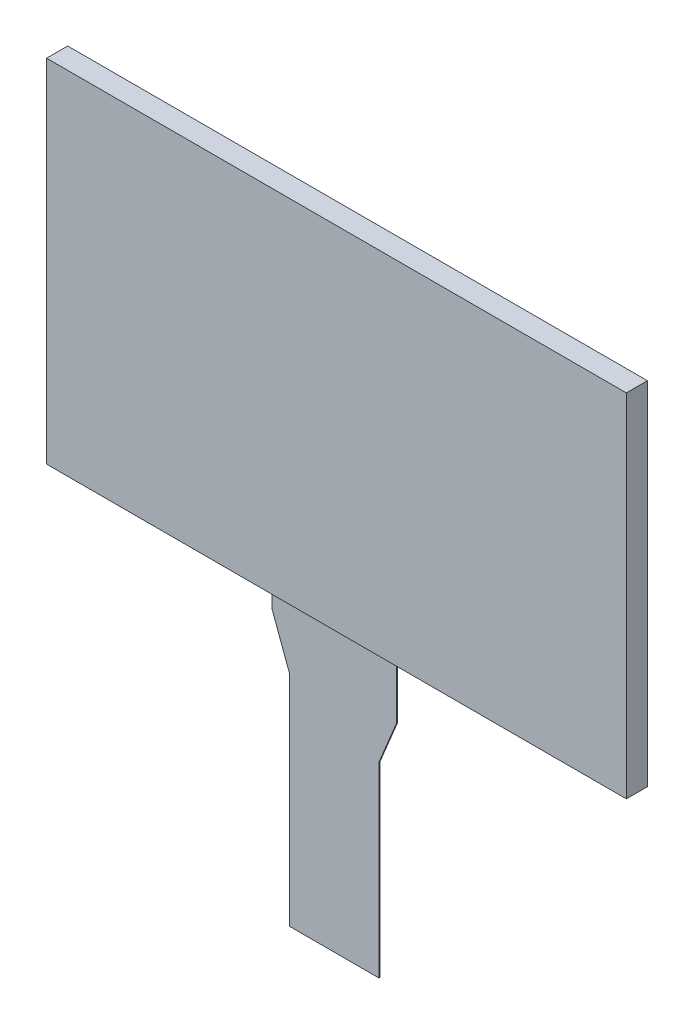
SolidWorks part; units mm, degrees
ref_plane "前视基准面" through (0, 0, 0) normal (0, 0, 1) x (1, 0, 0)
ref_plane "上视基准面" through (0, 0, 0) normal (0, 1, 0) x (1, 0, 0)
ref_plane "右视基准面" through (0, 0, 0) normal (1, 0, 0) x (0, 0, -1)
sketch "草图1" plane through (0, 0, 0) normal (0, 0, 1) x (1, 0, 0)
  line L0 (-185.7958, 0) -> (179.9924, 0) construction
  line L1 (-82.45, 50) -> (82.45, 50)
  line L2 (-82.45, 50) -> (-82.45, -50)
  line L3 (-82.45, -50) -> (82.45, -50)
  line L4 (82.45, 50) -> (82.45, -50)
  line L5 (0, 68.0465) -> (0, -103.7631) construction
  dimension "D1" = 164.9
  dimension "D2" = 100
extrude "外形" add sketch "草图1" along normal blind 6
sketch "草图2" plane through (0, 0, 0) normal (0, 0, 1) x (1, 0, 0)
  line L1 (-76.96, 46.43) -> (79.74, 46.43)
  line L2 (-76.96, 46.43) -> (-76.96, -42.67)
  line L3 (-76.96, -42.67) -> (79.74, -42.67)
  line L4 (79.74, 46.43) -> (79.74, -42.67)
  line L5 (-82.45, -50) -> (82.45, -50) construction
  line L6 (82.45, -50) -> (82.45, 50) construction
  dimension "D1" = 2.71
  dimension "D2" = 156.7
  dimension "D3" = 7.33
  dimension "D4" = 89.1
extrude "玻璃区域" cut sketch "草图2" along normal blind 0.1
sketch "显示区域示意" plane through (0, 0, 0.1) normal (0, 0, -1) x (-1, 0, 0)
  line L0 (-82.45, -50) -> (-82.45, 50) construction
  line L1 (-78.53, 45.22) -> (76.27, 45.22)
  line L2 (-78.53, 45.22) -> (-78.53, -40.7)
  line L3 (-78.53, -40.7) -> (76.27, -40.7)
  line L4 (76.27, 45.22) -> (76.27, -40.7)
  line L5 (82.45, -50) -> (-82.45, -50) construction
  dimension "D1" = 3.92
  dimension "D2" = 154.8
  dimension "D3" = 9.3
  dimension "D4" = 85.92
sketch "草图4" plane through (0, -50, 0) normal (0, -1, 0) x (1, 0, 0)
  line L0 (-1.5, 15.7706) -> (-1.5, -11.3723) construction
  line L1 (-19.25, 5.15) -> (16.25, 5.15)
  line L2 (-19.25, 5.15) -> (-19.25, 4.85)
  line L3 (-19.25, 4.85) -> (16.25, 4.85)
  line L4 (16.25, 5.15) -> (16.25, 4.85)
  line L5 (-26.7854, 5) -> (36.1476, 5) construction
  line L6 (-82.45, 6) -> (82.45, 6) construction
  line L8 (-82.45, 6) -> (-82.45, 0) construction
  dimension "D1" = 0.3
  dimension "D2" = 1
  dimension "D3" = 80.95
  dimension "D4" = 35.5
extrude "凸台-拉伸2" add sketch "草图4" along normal blind 80.15
sketch "草图5" plane through (0, 0, 4.85) normal (0, 0, -1) x (-1, 0, 0)
  line L0 (-16.25, -130.15) -> (-11.25, -130.15)
  line L1 (19.25, -130.15) -> (-16.25, -130.15) construction
  line L2 (-11.25, -130.15) -> (-11.25, -76.9872)
  line L3 (-11.25, -76.9872) -> (-16.25, -64.8671)
  line L4 (-16.25, -130.15) -> (-16.25, -50) construction
  line L5 (-16.25, -64.8671) -> (-16.25, -130.15)
  line L6 (19.25, -130.15) -> (14.25, -130.15)
  line L7 (14.25, -130.15) -> (14.25, -67.7396)
  line L8 (14.25, -67.7396) -> (19.25, -54.2554)
  line L9 (19.25, -130.15) -> (19.25, -50) construction
  line L10 (19.25, -54.2554) -> (19.25, -130.15)
  dimension "D1" = 5
  dimension "D2" = 25.5
extrude "切除-拉伸4" cut sketch "草图5" against normal through all
sketch "草图6" plane through (0, 0, 4.85) normal (0, 0, -1) x (-1, 0, 0)
  line L0 (14.25, -67.7396) -> (14.25, -130.15) construction
  line L1 (-11.25, -130.15) -> (14.25, -130.15)
  line L2 (-11.25, -130.15) -> (-11.25, -126.35)
  line L3 (-11.25, -126.35) -> (14.25, -126.35)
  line L4 (14.25, -130.15) -> (14.25, -126.35)
  dimension "D1" = 3.8
extrude "切除-拉伸5" cut sketch "草图6" against normal blind 0.05
